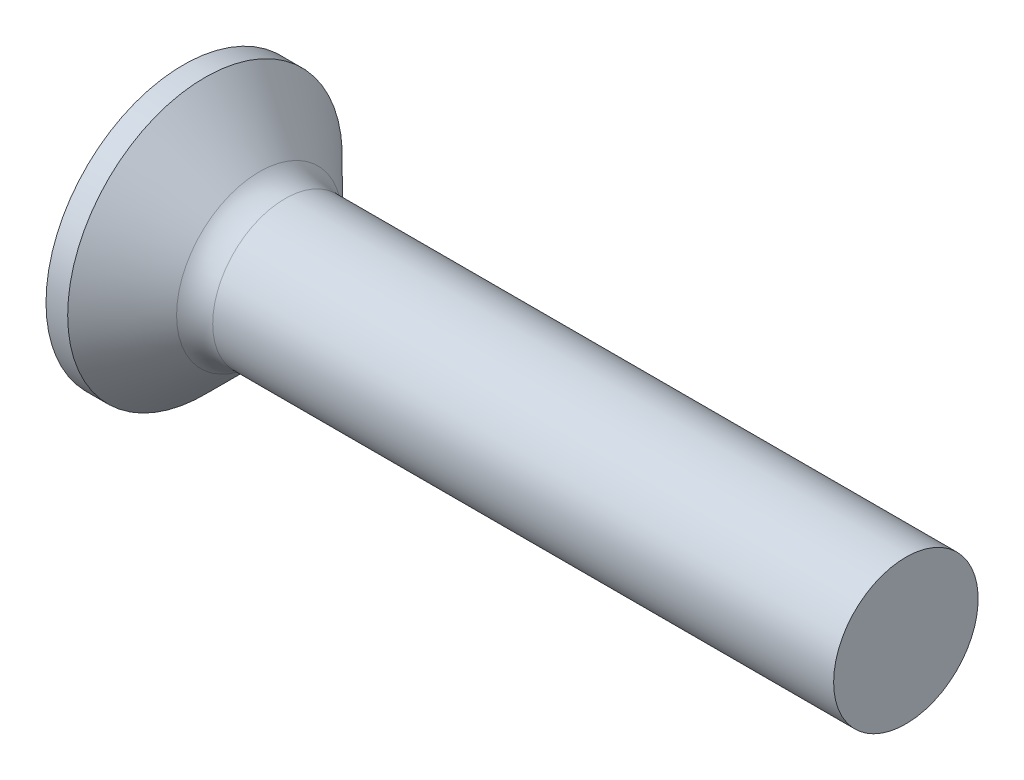
SolidWorks part; units mm, degrees
ref_plane "Plane1" through (0, 0, 0) normal (0, 0, 1) x (1, 0, 0)
ref_plane "Plane2" through (0, 0, 0) normal (0, 1, 0) x (1, 0, 0)
ref_plane "Plane3" through (0, 0, 0) normal (1, 0, 0) x (0, 0, -1)
sketch "BodySke" plane through (0, 0, 0) normal (0, 0, 1) x (1, 0, 0)
  line L0 (0, 0) -> (10.5, 0)
  line L1 (10.5, 0) -> (10.5, 1)
  line L2 (10.5, 1) -> (1.7, 1)
  line L3 (0.8, -1.9) -> (1.7, -1) construction
  line L4 (-15.875, 0) -> (82.55, 0) construction
  line L5 (0.8, 1.9) -> (1.7, 1)
  line L6 (2.1, 4.175) -> (2.1, -11.7) construction
  line L7 (0.5, 2.7793) -> (0.5, -13.0957) construction
  line L8 (0.8, 1.9) -> (0.5, 1.9)
  arc A0 (0, 0) -> (0.5, 1.9) centre (3.86, 0) cw
  dimension "Head_ang" = 90
  dimension "Diameter" = 2
  dimension "Advance" = 0.4
  dimension "Thread_nom" = 10
  dimension "Oval_ht" = 0.5
  dimension "Side_ht" = 1.2
  dimension "Head_dia" = 3.8
  dimension "Length" = 10
revolve "Base-Revolve" add sketch "BodySke" angle 360 about L4
cosmetic thread "ThreadCosmetic" [suppressed] parameters "Thread_length"=8.4, "Thread_minor"=1.548
fillet "Fillet1" radius 0.5 1 edges at (1.7, 0, 1)
sketch "Sketch3" plane through (0, 0, 0) normal (1, 0, 0) x (0, 0, -1)
  line L0 (0.24, -1.1) -> (-0.24, -1.1)
  line L1 (0.24, -1.1) -> (0.24, 1.1)
  line L2 (-0.24, 1.1) -> (0.24, 1.1)
  line L3 (-0.24, 1.1) -> (-0.24, -1.1)
  dimension "Cross_width" = 0.48
  dimension "D1" = 0.24
  dimension "Cross_dia" = 2.2
  dimension "D2" = 1.1
ref_plane "Plane4" through (1.4, 0, 0) normal (1, 0, 0) x (0, 0, -1)
sketch "Sketch4" plane through (1.4, 0, 0) normal (1, 0, 0) x (0, 0, -1)
  line L0 (0.24, -0.402) -> (-0.24, -0.402)
  line L1 (0.24, -0.402) -> (0.24, 0.402)
  line L2 (-0.24, 0.402) -> (0.24, 0.402)
  line L3 (-0.24, 0.402) -> (-0.24, -0.402)
  dimension "D1" = 0.48
  dimension "D2" = 0.804
  dimension "D3" = 0.24
  dimension "D4" = 0.402
loft "Recess" cut profiles "Sketch3", "Sketch4"
pattern_circular "RecPat" count 2 every 90 about axis through (0, 0, 0) along (1, 0, 0) of "Recess"
sketch "RecCorSke" plane through (0, 0, 0) normal (0, 0, 1) x (1, 0, 0)
  line L0 (-3.175, 0) -> (15.875, 0) construction
  line L2 (0, 0) -> (0, 0.4534)
  line L3 (0, 0.4534) -> (1.4, 0.3555)
  line L4 (1.4, 0.3555) -> (1.5155, 0)
  line L5 (1.5155, 0) -> (0, 0)
  dimension "Diameter" = 0.711
  dimension "Depth" = 1.4
  dimension "Draft_angle" = 4
  dimension "Bottom_angle" = 18
revolve "RecessCore" cut sketch "RecCorSke" angle 360 about L0
sketch "ThdSchSke" plane through (0, 0, 0) normal (0, 0, 1) x (1, 0, 0)
  line L0 (2.1, -0.774) -> (1.9418, -1)
  line L1 (2.1, -0.774) -> (2.2582, -1)
  line L2 (2.2582, -1) -> (2.2582, -1.25)
  line L3 (-3.175, 0) -> (5.1513, 0) construction
  line L5 (2.2582, -1.25) -> (1.9418, -1.25)
  line L6 (1.9418, -1.25) -> (1.9418, -1)
  dimension "Diameter" = 2
  dimension "SideAngle" = 55
  dimension "VeeAngle" = 70
  dimension "Thread_minor" = 1.548
  dimension "Overcut" = 2.5
  dimension "Start" = 2.1
revolve "ThreadSchematic" [suppressed] cut sketch "ThdSchSke" angle 360 about L3
pattern_linear "ThdSchPat" [suppressed]
equation "\"D1@Sketch3\" = \"Cross_width@Sketch3\" / 2"
equation "\"D2@Sketch3\" = \"Cross_dia@Sketch3\" / 2"
equation "\"Depth@RecCorSke\" = \"Cross_depth@Plane4\""
equation "\"D1@Sketch4\" = \"Cross_width@Sketch3\""
equation "\"D2@Sketch4\" = \"Cross_dia@Sketch3\" - 2.0 * \"Cross_depth@Plane4\" * tan(26.5  * 0.017453292)"
equation "\"D3@Sketch4\" = \"D1@Sketch4\" / 2"
equation "\"D4@Sketch4\" = \"D2@Sketch4\" / 2"
equation "\"Thread_length@ThreadCosmetic\" = ((sgn( (\"Length@BodySke\" - \"Advance@BodySke\" - \"Side_ht@BodySke\" ) - \"Thread_nom@BodySke\" )-1)*( (\"Length@BodySke\" - \"Advance@BodySke\" - \"Side_ht@BodySke\" ) - \"Thread_nom@BodySke\" ))/-2+ \"Thread_nom@BodySke\""
equation "\"Thread_minor@ThdSchSke\" = \"Thread_minor@ThreadCosmetic\""
equation "\"Diameter@ThdSchSke\" = \"Diameter@BodySke\""
equation "\"Overcut@ThdSchSke\" = \"Diameter@BodySke\" * 1.25"
equation "\"Start@ThdSchSke\" = \"Oval_ht@BodySke\" + \"Length@BodySke\" - \"Thread_length@ThreadCosmetic\"  '---Countersunk---"
equation "\"Num_threads@ThdSchPat\" = int( \"Thread_length@ThreadCosmetic\" / \"Advance@BodySke\" + 0.999 )  + 1"
equation "\"Advance@ThdSchPat\" = \"Thread_length@ThreadCosmetic\" /  (\"Num_threads@ThdSchPat\" - 1) 'relax it"
